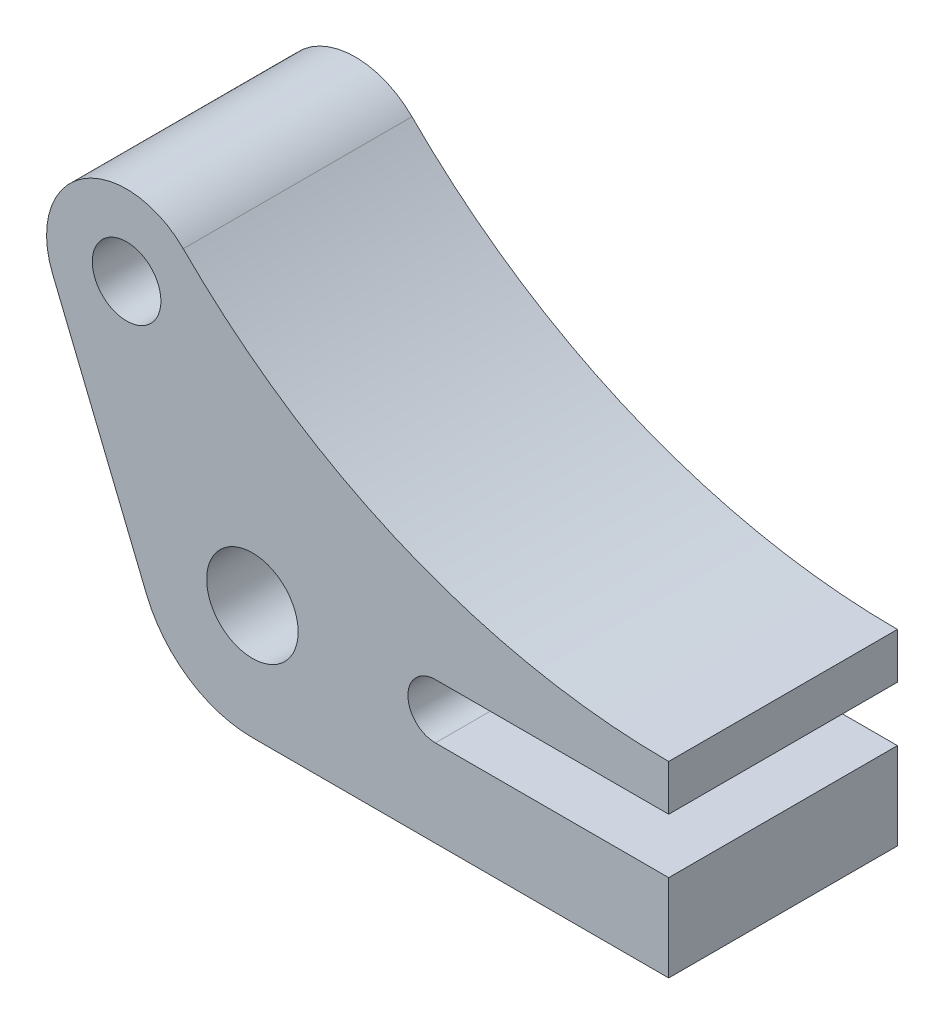
SolidWorks part; units mm, degrees
material "AISI 1020 Steel, Cold Rolled"
ref_plane "Front Plane" through (0, 0, 0) normal (0, 0, 1) x (1, 0, 0)
ref_plane "Top Plane" through (0, 0, 0) normal (0, 1, 0) x (1, 0, 0)
ref_plane "Right Plane" through (0, 0, 0) normal (1, 0, 0) x (0, 0, -1)
sketch "Sketch1" plane through (0, 0, 0) normal (0, 0, 1) x (1, 0, 0)
  line L0 (0, 0) -> (40, 0) construction
  line L2 (0, 0) -> (-27.5, 47.6314) construction
  line L3 (-43.7071, 41.0298) -> (-23.1529, -9.4309)
  line L4 (40, -6) -> (40, -25) construction
  line L5 (91.0121, -25) -> (0, -25)
  line L6 (40, -6) -> (91.0121, -6)
  line L7 (40, 6) -> (91.0121, 6)
  line L8 (91.0121, 16) -> (163.4358, 16)
  line L9 (91.0121, 16) -> (91.0121, 6)
  line L10 (91.0121, -25) -> (91.0121, -6)
  line L11 (91.0121, 16) -> (91.0121, -25) construction
  circle A0 centre (0, 0) radius 10
  arc A1 (-23.1529, -9.4309) -> (0, -25) centre (0, 0) ccw
  circle A3 centre (-27.5, 47.6314) radius 7.5
  arc A4 (-15.1181, 59.9983) -> (-43.7071, 41.0298) centre (-27.5, 47.6314) ccw
  arc A5 (-15.1181, 59.9983) -> (91.0121, 16) centre (91.0121, 166) ccw
  arc A6 (40, 6) -> (40, -6) centre (40, 0) ccw
  dimension "D4" = 35
  dimension "D8" = 10
  dimension "D9" = 19
  dimension "D10" = 41
extrude "Boss-Extrude1" add sketch "Sketch1" along normal mid plane 50 contours A6 L7 L9 A5 A4 L3 A1 L5 L10 L6 A3 A0
